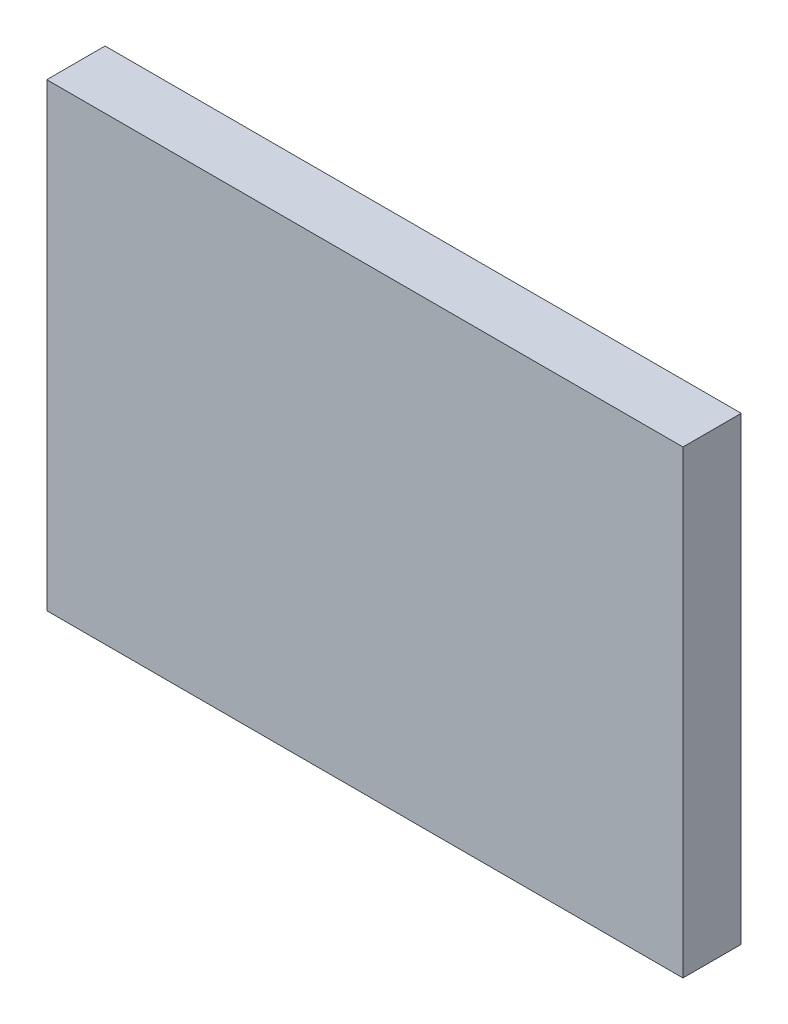
SolidWorks part; units mm, degrees
ref_plane "Ebene vorne" through (0, 0, 0) normal (0, 0, 1) x (1, 0, 0)
ref_plane "Ebene oben" through (0, 0, 0) normal (0, 1, 0) x (1, 0, 0)
ref_plane "Ebene rechts" through (0, 0, 0) normal (1, 0, 0) x (0, 0, -1)
sketch "Skizze1" plane through (0, 0, 0) normal (0, 0, 1) x (1, 0, 0)
  line L1 (6.912, 0) -> (0, 0)
  line L2 (6.912, 0) -> (6.912, 3.888)
  line L3 (6.912, 3.888) -> (0, 3.888)
  line L4 (0, 0) -> (0, 3.888)
  dimension "D1" = 6.912
  dimension "D2" = 3.888
extrude "Aufsatz-Linear austragen1" add sketch "Skizze1" along normal blind 1 contours L2 L1 L4 L3
sketch "Skizze2" plane through (0, 0, 1) normal (0, 0, 1) x (1, 0, 0)
  line L0 (6.912, 3.888) -> (0, 3.888) construction
  line L1 (-2, 5.888) -> (8.912, 5.888)
  line L2 (-2, 5.888) -> (-2, -2)
  line L3 (-2, -2) -> (8.912, -2)
  line L4 (8.912, 5.888) -> (8.912, -2)
  line L5 (6.912, 0) -> (6.912, 3.888) construction
  line L6 (6.912, 0) -> (0, 0) construction
  line L7 (0, 0) -> (0, 3.888) construction
  dimension "D1" = 2
  dimension "D2" = 2
  dimension "D3" = 2
  dimension "D4" = 2
extrude "Aufsatz-Linear austragen2" add sketch "Skizze2" along normal blind 1 contours L2 L1 L4 L3
sketch3d "3D-Skizze1"
  point P0 (3.0972, 2.5054, 0)
sketch "Skizze3" plane through (0, 0, 0) normal (0, 0, -1) x (-1, 0, 0)
  line L1 (-3.956, 2.444) -> (-2.956, 2.444)
  line L2 (-3.956, 2.444) -> (-3.956, 1.444)
  line L3 (-3.956, 1.444) -> (-2.956, 1.444)
  line L4 (-2.956, 2.444) -> (-2.956, 1.444)
  line L5 (-6.912, 0) -> (-6.912, 3.888) construction
  line L7 (0, 0) -> (0, 3.888) construction
  line L9 (-6.912, 0) -> (0, 0) construction
  line L10 (-3.456, 3.888) -> (-3.456, 0) construction
  line L11 (-6.912, 3.888) -> (0, 3.888) construction
  line L12 (-6.912, 0) -> (0, 0) construction
  line L13 (-6.912, 1.944) -> (0, 1.944) construction
  line L14 (0, 0) -> (0, 3.888) construction
  line L15 (-3.956, 2.444) -> (-2.956, 1.444) construction
  line L16 (-3.956, 1.444) -> (-2.956, 2.444) construction
  line L17 (-3.956, 1.944) -> (-3.456, 2.444)
  line L18 (-3.956, 1.944) -> (-3.4611, 1.4491)
  line L19 (-3.456, 2.444) -> (-2.9611, 1.9491)
  line L20 (-3.4611, 1.4491) -> (-2.9611, 1.9491)
  point P22 (-3.456, 1.944)
  point P23 (-3.456, 1.944)
  dimension "D1" = 1
  dimension "D2" = 1
  dimension "D4" = 2.956
  dimension "D6" = 1.444
extrude "Aufsatz-Linear austragen3" add sketch "Skizze3" along normal blind 0.0306 contours L18 L20 L19 L17
sketch "Skizze4" plane through (1.006, -1.006, 0) normal (0.7071, -0.7071, 0) x (0, 0, -1)
  line L0 (0.0306, 4.1719) -> (0, 3.472) construction
  line L1 (0.0153, 3.822) -> (0.0306, 3.472)
  line L2 (0.0306, 3.472) -> (0.0306, 4.1719)
  line L3 (0.0306, 4.1719) -> (0.0153, 3.822)
extrude "Schnitt-Linear austragen1" cut sketch "Skizze4" against normal blind 10 contours L3 L1 L2
